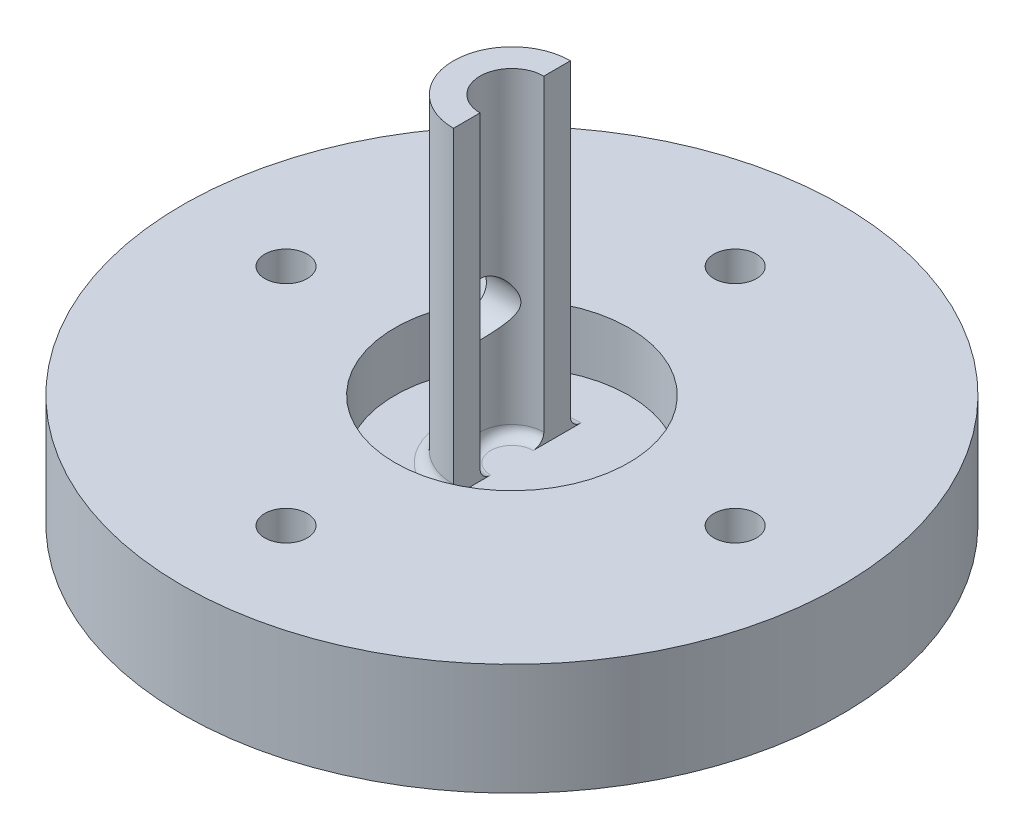
SolidWorks part; units mm, degrees
ref_plane "Front Plane" through (0, 0, 0) normal (0, 0, 1) x (1, 0, 0)
ref_plane "Top Plane" through (0, 0, 0) normal (0, 1, 0) x (1, 0, 0)
ref_plane "Right Plane" through (0, 0, 0) normal (1, 0, 0) x (0, 0, -1)
sketch "Sketch1" plane through (0, 0, 0) normal (0, 1, 0) x (1, 0, 0)
  line L0 (0, 5.5) -> (0, 3)
  line L1 (0, -3) -> (0, -5.5)
  arc A0 (0, 5.5) -> (0, -5.5) centre (0, 0) ccw
  arc A1 (0, 3) -> (0, -3) centre (0, 0) ccw
  dimension "D1" = 6
  dimension "D2" = 11
extrude "Boss-Extrude2" add sketch "Sketch1" along normal blind 30
sketch "Sketch2" plane through (0, 0, 0) normal (0, 1, 0) x (1, 0, 0)
  circle A0 centre (0, 0) radius 31
  arc A1 (0, 5.5) -> (0, -5.5) centre (0, 0) ccw construction
  dimension "D1" = 62
extrude "Boss-Extrude3" add sketch "Sketch2" against normal blind 5
fillet "Fillet1" radius 1 1 edges at (-5.5, 0, 0)
sketch "Sketch3" plane through (0, 0, 0) normal (0, 1, 0) x (1, 0, 0)
  circle A0 centre (0, 0) radius 11
  circle A1 centre (0, 0) radius 31
  circle A2 centre (0, 0) radius 31 construction
  dimension "D1" = 22
extrude "Boss-Extrude4" add sketch "Sketch3" along normal blind 5.5
sketch "Sketch4" plane through (0, 5.5, 0) normal (0, 1, 0) x (1, 0, 0)
  line L0 (0, 31) -> (0, 11) construction
  circle A0 centre (0, 21) radius 2
  circle A1 centre (0, 0) radius 31 construction
  circle A2 centre (0, 0) radius 11 construction
  circle A3 centre (21.125, -0.125) radius 2
  circle A4 centre (0, -21.25) radius 2
  circle A5 centre (-21.125, -0.125) radius 2
  dimension "D2" = 4
  dimension "D1" = 4
extrude "Cut-Extrude1" cut sketch "Sketch4" against normal through all both and the other way through all
sketch "Sketch6" plane through (0, 0, 0) normal (1, 0, 0) x (0, 0, -1)
  line L0 (0, 8.5) -> (0, 0) construction
  line L3 (-6.5, 0) -> (-3, 0) construction
  line L4 (3, 0) -> (-3, 0) construction
  circle A0 centre (0, 11) radius 2.5
  dimension "D2" = 5
  dimension "D1" = 8.5
extrude "Cut-Extrude2" cut sketch "Sketch6" against normal through all both and the other way through all
fillet "Fillet2" radius 1 1 edges at (-3, 0, 0)
